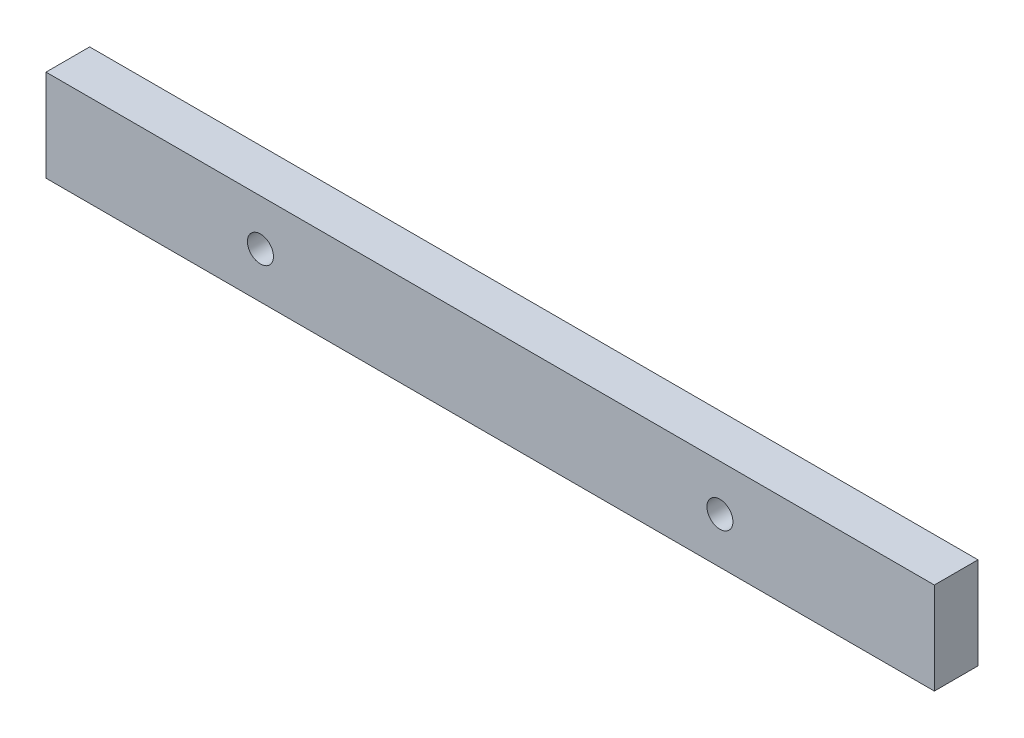
SolidWorks part; units mm, degrees
ref_plane "Front" through (0, 0, 0) normal (0, 0, 1) x (1, 0, 0)
ref_plane "Top" through (0, 0, 0) normal (0, 1, 0) x (1, 0, 0)
ref_plane "Right" through (0, 0, 0) normal (1, 0, 0) x (0, 0, -1)
sketch "Sketch1" plane through (0, 0, 0) normal (0, 0, 1) x (1, 0, 0)
  line L1 (-29, 3) -> (29, 3)
  line L2 (-29, 3) -> (-29, -3)
  line L3 (-29, -3) -> (29, -3)
  line L4 (29, 3) -> (29, -3)
  line L5 (-29, 3) -> (29, -3) construction
  line L6 (-29, -3) -> (29, 3) construction
  point P0 (0, 0)
  dimension "D1" = 6
  dimension "D2" = 58
extrude "Boss-Extrude1" add sketch "Sketch1" along normal blind 2.85
sketch "Sketch2" plane through (0, 0, 2.85) normal (0, 0, 1) x (1, 0, 0)
  line L0 (-15, 0) -> (0, 0) construction
  line L1 (0, 0) -> (15, 0) construction
  circle A0 centre (15, 0) radius 0.8494
  circle A1 centre (-15, 0) radius 0.8494
  dimension "D1" = 30
extrude "Cut-Extrude1" cut sketch "Sketch2" against normal through all
